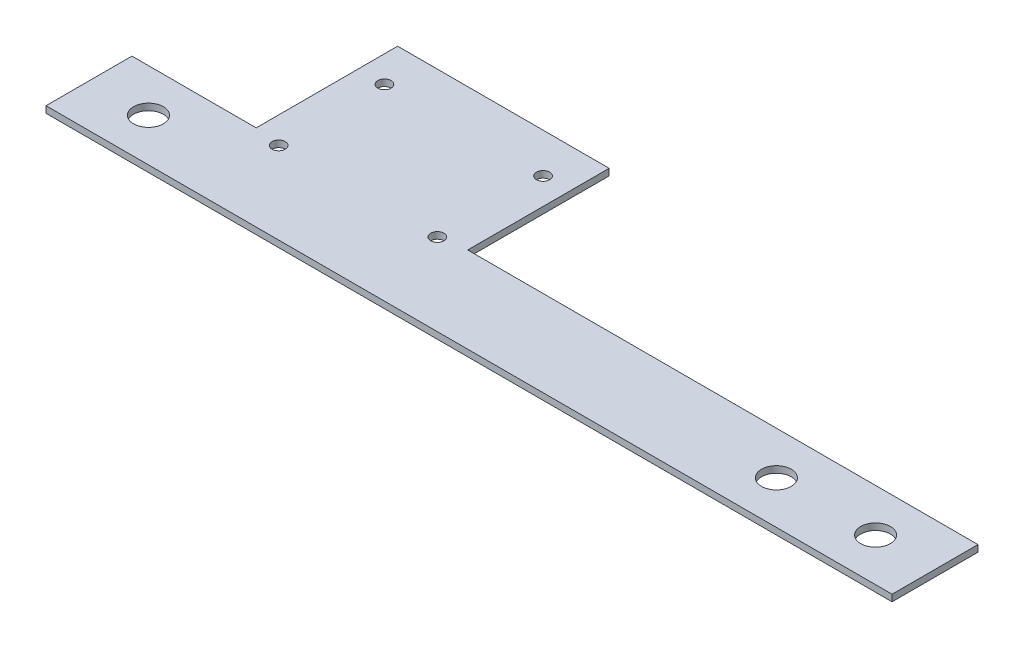
SolidWorks part; units mm, degrees
ref_plane "Front Plane" through (0, 0, 0) normal (0, 0, 1) x (1, 0, 0)
ref_plane "Top Plane" through (0, 0, 0) normal (0, 1, 0) x (1, 0, 0)
ref_plane "Right Plane" through (0, 0, 0) normal (1, 0, 0) x (0, 0, -1)
sketch "Sketch1" plane through (0, 0, 0) normal (0, 1, 0) x (1, 0, 0)
  line L0 (0, 0) -> (406.4, 0)
  line L1 (406.4, 0) -> (406.4, 41.275)
  line L2 (406.4, 41.275) -> (161.29, 41.275)
  line L3 (161.29, 41.275) -> (161.29, 109.22)
  line L4 (161.29, 109.22) -> (59.69, 109.22)
  line L5 (59.69, 109.22) -> (59.69, 41.275)
  line L6 (59.69, 41.275) -> (0, 41.275)
  line L7 (0, 41.275) -> (0, 0)
  dimension "D1" = 406.4
  dimension "D2" = 41.275
  dimension "D3" = 109.22
  dimension "D4" = 245.11
  dimension "D5" = 101.6
extrude "Boss-Extrude1" add sketch "Sketch1" along normal blind 3.175
sketch "Sketch2" plane through (0, 3.175, 0) normal (0, 1, 0) x (1, 0, 0)
  line L0 (28.575, 20.6375) -> (377.825, 20.6375) construction
  line L1 (0, 41.275) -> (0, 0) construction
  line L2 (0, 0) -> (406.4, 0) construction
  line L3 (406.4, 0) -> (406.4, 41.275) construction
  line L4 (161.29, 109.22) -> (59.69, 109.22) construction
  line L5 (59.69, 109.22) -> (59.69, 41.275) construction
  line L6 (72.39, 90.17) -> (148.59, 90.17) construction
  line L7 (148.59, 90.17) -> (148.59, 39.37) construction
  line L8 (148.59, 39.37) -> (72.39, 39.37) construction
  line L9 (72.39, 39.37) -> (72.39, 90.17) construction
  line L10 (161.29, 41.275) -> (161.29, 109.22) construction
  circle A0 centre (28.575, 20.6375) radius 7.1437
  circle A1 centre (72.39, 90.17) radius 3.175
  circle A2 centre (330.2, 20.6375) radius 7.1438
  circle A3 centre (377.825, 20.6375) radius 7.1438
  circle A4 centre (72.39, 39.37) radius 3.175
  circle A5 centre (148.59, 39.37) radius 3.175
  circle A6 centre (148.59, 90.17) radius 3.175
  dimension "D1" = 14.2875
  dimension "D3" = 6.35
  dimension "D2" = 28.575
  dimension "D4" = 20.6375
  dimension "D5" = 28.575
  dimension "D6" = 76.2
  dimension "D7" = 19.05
  dimension "D8" = 69.85
  dimension "D9" = 12.7
  dimension "D10" = 12.7
extrude "Cut-Extrude1" cut sketch "Sketch2" against normal through all
